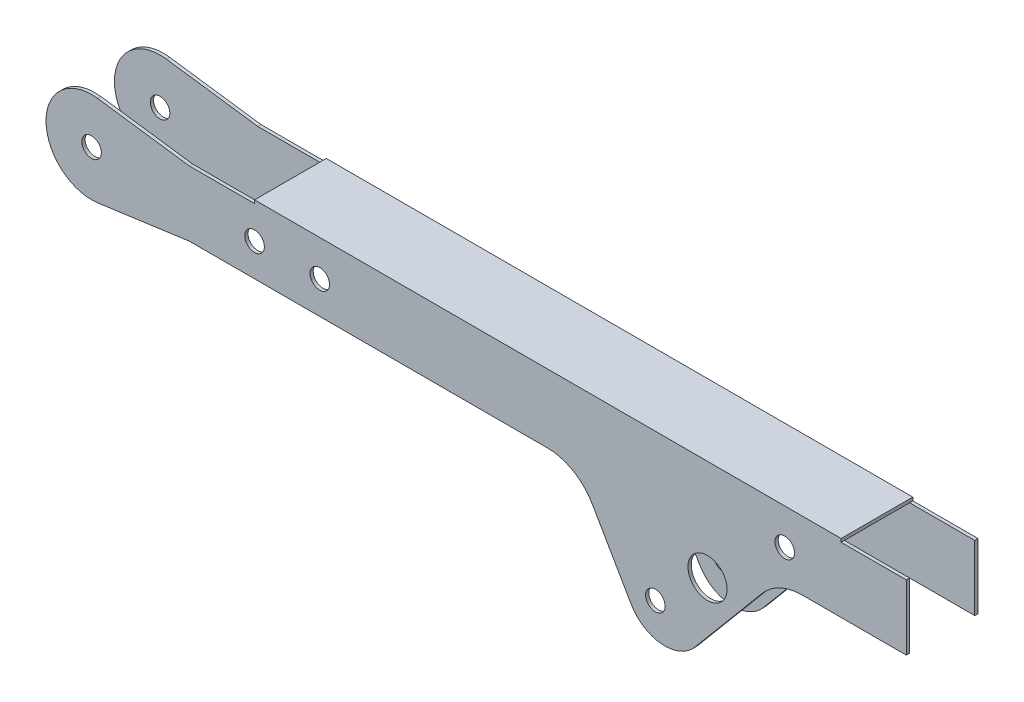
SolidWorks part; units mm, degrees
material "7075-T6，板材(SS)"
ref_plane "前视基准面" through (0, 0, 0) normal (0, 0, 1) x (1, 0, 0)
ref_plane "上视基准面" through (0, 0, 0) normal (0, 1, 0) x (1, 0, 0)
ref_plane "右视基准面" through (0, 0, 0) normal (1, 0, 0) x (0, 0, -1)
sketch "草图1" plane through (0, 0, 0) normal (0, 0, 1) x (1, 0, 0)
  line L0 (-28.9376, 12.8639) -> (81.0624, 12.8639)
  line L1 (-28.9376, 2.8639) -> (30.5624, 2.8639)
  line L2 (-49.4416, 7.8639) -> (82.0027, 7.8639) construction
  line L3 (-28.9376, 12.8639) -> (-42.9824, 14.7984)
  line L4 (-28.9376, 2.8639) -> (-42.9824, 0.9293)
  line L5 (30.5624, 2.8639) -> (43.107, -18.864)
  line L6 (43.107, -18.864) -> (61.3388, 2.8639)
  line L7 (81.0624, 12.8639) -> (81.0624, 2.8639)
  line L8 (61.3388, 2.8639) -> (81.0624, 2.8639)
  arc A0 (-42.9824, 14.7984) -> (-42.9824, 0.9293) centre (-43.9376, 7.8639) ccw
  circle A1 centre (-43.9376, 7.8639) radius 1.5
  circle A2 centre (42.5624, -9.1361) radius 1.5
  circle A3 centre (50.5624, -2.1361) radius 3
  circle A4 centre (-18.9376, 7.8639) radius 1.5
  circle A5 centre (-8.9376, 7.8639) radius 1.5
  circle A6 centre (62.4094, 7.8639) radius 1.5
  dimension "D1" = 3
  dimension "D2" = 14
  dimension "D12" = 3
  dimension "D14" = 6
  dimension "D20" = 3
  dimension "D21" = 3
  dimension "D22" = 3
  dimension "D3" = 110
  dimension "D4" = 12
  dimension "D5" = 10
  dimension "D6" = 15
  dimension "D7" = 15
  dimension "D8" = 5
  dimension "D9" = 86.5
  dimension "D10" = 60
  dimension "D11" = 50
  dimension "D15" = 5
  dimension "D16" = 20
  dimension "D17" = 12
  dimension "D18" = 25
  dimension "D19" = 35
extrude "凸台-拉伸1" add sketch "草图1" along normal blind 0.5
ref_plane "基准面1" through (0, 0, -10) normal (0, 0, 1) x (1, 0, 0)
sketch "草图3" plane through (0, 0, -10) normal (0, 0, 1) x (1, 0, 0)
  line L8 (43.107, -18.864) -> (61.3388, 2.8639)
  line L9 (61.3388, 2.8639) -> (81.0624, 2.8639)
  line L10 (81.0624, 2.8639) -> (81.0624, 12.8639)
  line L11 (81.0624, 12.8639) -> (-28.9376, 12.8639)
  line L12 (-28.9376, 12.8639) -> (-42.9824, 14.7984)
  line L13 (-42.9824, 0.9293) -> (-28.9376, 2.8639)
  line L14 (-28.9376, 2.8639) -> (30.5624, 2.8639)
  line L15 (30.5624, 2.8639) -> (43.107, -18.864)
  line L16 (43.107, -18.864) -> (61.3388, 2.8639)
  line L17 (61.3388, 2.8639) -> (81.0624, 2.8639)
  line L18 (81.0624, 2.8639) -> (81.0624, 12.8639)
  line L19 (81.0624, 12.8639) -> (-28.9376, 12.8639)
  line L20 (-28.9376, 12.8639) -> (-42.9824, 14.7984)
  line L21 (-42.9824, 0.9293) -> (-28.9376, 2.8639)
  line L22 (-28.9376, 2.8639) -> (30.5624, 2.8639)
  line L23 (30.5624, 2.8639) -> (43.107, -18.864)
  circle A1 centre (50.5624, -2.1361) radius 3
  circle A2 centre (50.5624, -2.1361) radius 3
  circle A3 centre (42.5624, -9.1361) radius 1.5
  circle A4 centre (42.5624, -9.1361) radius 1.5
  circle A5 centre (-43.9376, 7.8639) radius 1.5
  circle A6 centre (-43.9376, 7.8639) radius 1.5
  circle A7 centre (62.4094, 7.8639) radius 1.5
  circle A8 centre (62.4094, 7.8639) radius 1.5
  circle A9 centre (-8.9376, 7.8639) radius 1.5
  circle A10 centre (-8.9376, 7.8639) radius 1.5
  circle A11 centre (-18.9376, 7.8639) radius 1.5
  circle A12 centre (-18.9376, 7.8639) radius 1.5
  arc A13 (-42.9824, 14.7984) -> (-42.9824, 0.9293) centre (-43.9376, 7.8639) ccw
  arc A14 (-42.9824, 14.7984) -> (-42.9824, 0.9293) centre (-43.9376, 7.8639) ccw
  dimension "D1" = 0
  dimension "D2" = 0
  dimension "D3" = 0
  dimension "D4" = 0
  dimension "D5" = 0
  dimension "D6" = 0
  dimension "D7" = 0
extrude "凸台-拉伸2" add sketch "草图3" against normal blind 0.5 separate body
ref_plane "基准面3" through (0, 12.8639, 0) normal (0, 1, 0) x (1, 0, 0)
sketch "草图4" plane through (0, 12.8639, 0) normal (0, 1, 0) x (1, 0, 0)
  line L0 (71.0624, 10.5) -> (71.0624, -0.5)
  line L1 (71.0624, -0.5) -> (-18.9376, -0.5)
  line L2 (81.0624, -0.5) -> (-28.9376, -0.5) construction
  line L3 (-18.9376, -0.5) -> (-18.9376, 10.5)
  line L4 (81.0624, 10.5) -> (-28.9376, 10.5) construction
  line L5 (-18.9376, 10.5) -> (71.0624, 10.5)
  line L6 (-43.9376, 10.5) -> (-43.9376, 10) construction
  line L8 (81.0624, 13.7104) -> (81.0624, -2.5495) construction
  dimension "D1" = 25
  dimension "D2" = 10
extrude "凸台-拉伸3" add sketch "草图4" along normal blind 0.5
fillet "圆角1" radius 8 4 edges at (30.5624, 2.8639, 0.25) (30.5624, 2.8639, -10.25) (61.3388, 2.8639, 0.25) (61.3388, 2.8639, -10.25)
fillet "圆角2" radius 6 2 edges at (43.107, -18.864, -10.25) (43.107, -18.864, 0.25)
